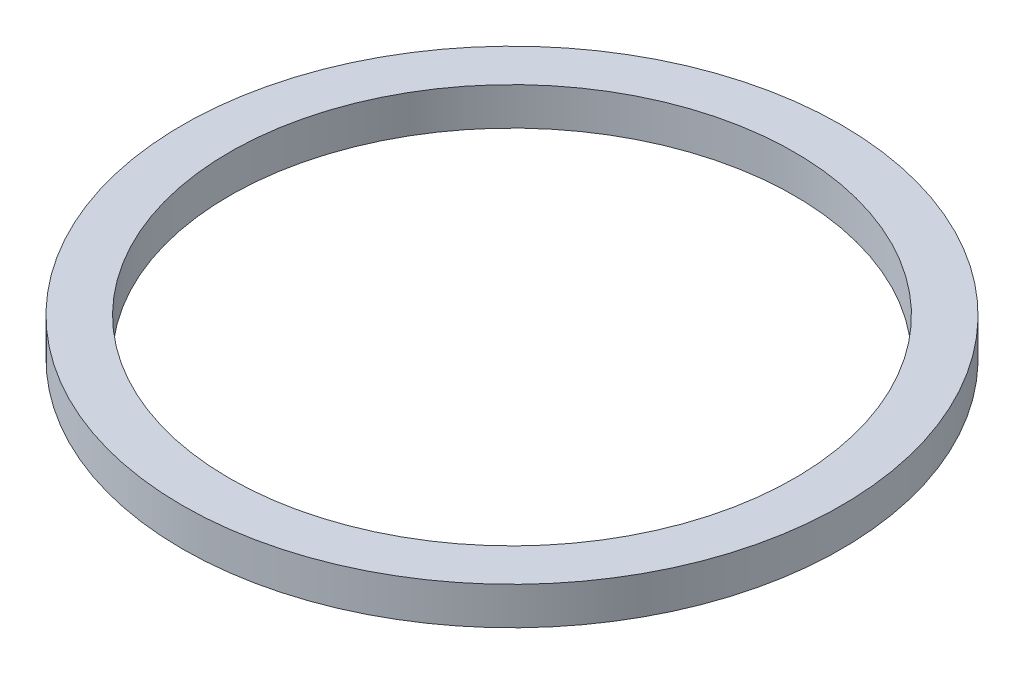
SolidWorks part; units mm, degrees
ref_plane "前视基准面" through (0, 0, 0) normal (0, 0, 1) x (1, 0, 0)
ref_plane "上视基准面" through (0, 0, 0) normal (0, 1, 0) x (1, 0, 0)
ref_plane "右视基准面" through (0, 0, 0) normal (1, 0, 0) x (0, 0, -1)
other "Configuration Table"
sketch "草图1" plane through (0, 0, 0) normal (0, 1, 0) x (1, 0, 0)
  circle A0 centre (0, 0) radius 17.5
  circle A1 centre (0, 0) radius 15
  dimension "D1" = 35
  dimension "D2" = 30
extrude "凸台-拉伸1" add sketch "草图1" along normal blind 2
